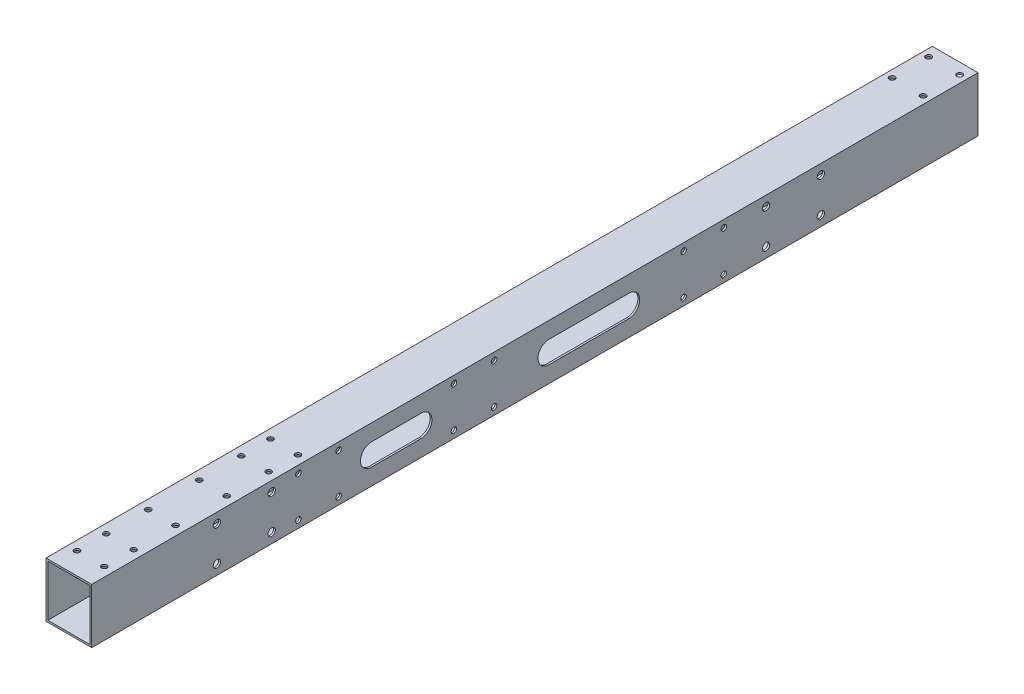
SolidWorks part; units mm, degrees
material "6063-T5"
ref_plane "前视基准面" through (0, 0, 0) normal (0, 0, 1) x (1, 0, 0)
ref_plane "上视基准面" through (0, 0, 0) normal (0, 1, 0) x (1, 0, 0)
ref_plane "右视基准面" through (0, 0, 0) normal (1, 0, 0) x (0, 0, -1)
sketch "草图1" plane through (0, 0, 0) normal (0, 0, 1) x (1, 0, 0)
  line L0 (-11.5, -14) -> (-11.5, 14)
  line L1 (-12.5, -15) -> (12.5, -15)
  line L2 (-12.5, -15) -> (-12.5, 15)
  line L3 (-12.5, 15) -> (12.5, 15)
  line L4 (12.5, -15) -> (12.5, 15)
  line L5 (0, 15) -> (0, -15) construction
  line L6 (-12.5, 0) -> (12.5, 0) construction
  line L7 (-11.5, 14) -> (11.5, 14)
  line L8 (11.5, -14) -> (11.5, 14)
  line L9 (-11.5, -14) -> (11.5, -14)
  point P0 (0, 0)
  dimension "D1" = 25
  dimension "D2" = 30
  dimension "D3" = 1
extrude "凸台-拉伸1" add sketch "草图1" along normal mid plane 485
sketch "草图4" plane through (0, 14, 0) normal (0, -1, 0) x (1, 0, 0)
  circle A0 centre (7.5, 214.55) radius 1.5 construction
  circle A1 centre (-7.5, 214.55) radius 1.5 construction
  circle A2 centre (7.5, 230.55) radius 1.5 construction
  circle A3 centre (-7.5, 230.55) radius 1.5 construction
  circle A4 centre (7.5, 214.55) radius 1.5
  circle A5 centre (-7.5, 214.55) radius 1.5
  circle A6 centre (7.5, 230.55) radius 1.5
  circle A7 centre (-7.5, 230.55) radius 1.5
  circle A8 centre (7.5, 124.65) radius 1.5 construction
  circle A9 centre (7.5, 140.65) radius 1.5 construction
  circle A10 centre (-7.5, 140.65) radius 1.5 construction
  circle A11 centre (-7.5, 124.65) radius 1.5 construction
  circle A12 centre (7.5, 124.65) radius 1.5
  circle A13 centre (7.5, 140.65) radius 1.5
  circle A14 centre (-7.5, 140.65) radius 1.5
  circle A15 centre (-7.5, 124.65) radius 1.5
extrude "切除-拉伸3" cut sketch "草图4" against normal mid plane 10
sketch "草图5" plane through (0, 15, 0) normal (0, 1, 0) x (1, 0, 0)
  line L0 (7.5, -140.65) -> (7.5, -214.55) construction
  line L1 (-7.5, -191.6) -> (7.5, -191.6) construction
  line L2 (-7.5, -191.6) -> (-7.5, -163.6) construction
  line L3 (-7.5, -163.6) -> (7.5, -163.6) construction
  line L4 (7.5, -191.6) -> (7.5, -163.6) construction
  line L5 (0, -163.6) -> (0, -191.6) construction
  line L6 (-7.5, -177.6) -> (7.5, -177.6) construction
  line L7 (12.5, -242.5) -> (12.5, 242.5) construction
  line L8 (-12.5, -242.5) -> (-12.5, 242.5) construction
  line L9 (7.5, -177.6) -> (-11.4517, -177.6) construction
  circle A0 centre (-7.5, -163.6) radius 1.525
  circle A1 centre (7.5, -163.6) radius 1.525
  circle A2 centre (-7.5, -191.6) radius 1.525
  circle A3 centre (7.5, -191.6) radius 1.525
  point P0 (0, -177.6)
  dimension "D4" = 3.05
  dimension "D1" = 5
  dimension "D2" = 5
  dimension "D3" = 28
extrude "切除-拉伸4" cut sketch "草图5" against normal mid plane 160
sketch "草图6" plane through (-12.5, 0, 0) normal (-1, 0, 0) x (0, 0, 1)
  line L0 (-79.9, 231.9) -> (-79.9, -138.1) construction
  line L1 (-104.9, 231.9) -> (-104.9, -138.1) construction
  line L2 (-79.9, 15) -> (-79.9, -15)
  line L3 (-104.9, 15) -> (-104.9, -15)
  line L4 (130.9, 231.9) -> (130.9, -138.1) construction
  line L5 (105.9, 231.9) -> (105.9, -138.1) construction
  line L6 (130.9, 15) -> (130.9, -15)
  line L7 (105.9, 15) -> (105.9, -15)
  line L8 (242.5, 15) -> (-242.5, 15) construction
  line L9 (242.5, -15) -> (-242.5, -15) construction
sketch "草图7" plane through (-12.5, 0, 0) normal (-1, 0, 0) x (0, 0, 1)
  line L0 (30.295, 205.9) -> (30.295, -116.65) construction
  line L1 (30.295, 15) -> (30.295, -15)
  line L2 (36.295, -116.65) -> (36.295, 205.9)
  line L3 (-10.295, 205.9) -> (-10.295, -116.65)
  line L4 (36.295, -15) -> (36.295, 15)
  line L44 (242.5, -15) -> (-242.5, -15) construction
  line L45 (242.5, 15) -> (-242.5, 15) construction
  line L46 (36.295, -15) -> (30.295, -15)
  line L47 (36.295, 15) -> (30.295, 15)
  line L48 (33.295, 15) -> (33.295, -15) construction
  arc A2 (-10.295, -116.65) -> (36.295, -116.65) centre (13, -116.65) ccw
  arc A3 (36.295, 205.9) -> (-10.295, 205.9) centre (13, 205.9) ccw
  dimension "D1" = 0
sketch "草图8" plane through (0, 15, 0) normal (0, 1, 0) x (1, 0, 0)
  circle A0 centre (8.5, 236.5) radius 1.55 construction
  circle A1 centre (-8.5, 236.5) radius 1.55 construction
  circle A2 centre (-8.5, 216.5) radius 1.55 construction
  circle A3 centre (8.5, 216.5) radius 1.55 construction
  circle A4 centre (8.5, 236.5) radius 1.55
  circle A5 centre (-8.5, 236.5) radius 1.55
  circle A6 centre (-8.5, 216.5) radius 1.55
  circle A7 centre (8.5, 216.5) radius 1.55
extrude "切除-拉伸5" cut sketch "草图8" against normal blind 59
sketch "草图9" plane through (12.5, 0, 0) normal (1, 0, 0) x (0, 0, -1)
  circle A0 centre (103.4, -11) radius 1.505 construction
  circle A1 centre (103.4, 11) radius 1.505 construction
  circle A2 centre (81.4, 11) radius 1.505 construction
  circle A3 centre (81.4, -11) radius 1.505 construction
  circle A4 centre (103.4, -11) radius 1.505
  circle A5 centre (103.4, 11) radius 1.505
  circle A6 centre (81.4, 11) radius 1.505
  circle A7 centre (81.4, -11) radius 1.505
  circle A8 centre (-44.295, -11) radius 1.505 construction
  circle A9 centre (-44.295, 11) radius 1.505 construction
  circle A10 centre (-22.295, 11) radius 1.505 construction
  circle A11 centre (-22.295, -11) radius 1.505 construction
  circle A12 centre (-44.295, -11) radius 1.505
  circle A13 centre (-44.295, 11) radius 1.505
  circle A14 centre (-22.295, 11) radius 1.505
  circle A15 centre (-22.295, -11) radius 1.505
  circle A16 centre (-107.4, -11) radius 1.505 construction
  circle A17 centre (-129.4, -11) radius 1.505 construction
  circle A18 centre (-107.4, 11) radius 1.505 construction
  circle A19 centre (-129.4, 11) radius 1.505 construction
  circle A20 centre (-107.4, -11) radius 1.505
  circle A21 centre (-129.4, -11) radius 1.505
  circle A22 centre (-107.4, 11) radius 1.505
  circle A23 centre (-129.4, 11) radius 1.505
extrude "切除-拉伸6" cut sketch "草图9" against normal blind 51
sketch "草图10" plane through (-12.5, 0, 0) normal (-1, 0, 0) x (0, 0, 1)
  line L0 (-51.4, 0) -> (-7.705, 0) construction
  line L1 (-51.4, 6) -> (-7.705, 6)
  line L2 (-51.4, -6) -> (-7.705, -6)
  line L3 (62.295, 0) -> (89.4, 0) construction
  line L4 (62.295, 6) -> (89.4, 6)
  line L5 (62.295, -6) -> (89.4, -6)
  arc A0 (-51.4, 6) -> (-51.4, -6) centre (-51.4, 0) ccw
  arc A1 (-7.705, -6) -> (-7.705, 6) centre (-7.705, 0) ccw
  circle A2 centre (-81.4, -11) radius 1.505 construction
  circle A3 centre (22.295, 11) radius 1.505 construction
  arc A4 (62.295, 6) -> (62.295, -6) centre (62.295, 0) ccw
  arc A5 (89.4, -6) -> (89.4, 6) centre (89.4, 0) ccw
  circle A6 centre (44.295, 11) radius 1.505 construction
  circle A7 centre (107.4, 11) radius 1.505 construction
  point P3 (-29.5525, 0)
  point P14 (75.8475, 0)
  dimension "D2" = 6
  dimension "D1" = 30
  dimension "D3" = 30
  dimension "D4" = 18
  dimension "D5" = 18
extrude "切除-拉伸7" cut sketch "草图10" against normal blind 146
sketch "草图11" plane through (12.5, 0, 0) normal (1, 0, 0) x (0, 0, -1)
  circle A0 centre (156.5, 9.5) radius 2 construction
  circle A1 centre (126.5, 9.5) radius 2 construction
  circle A2 centre (126.5, -9.5) radius 2 construction
  circle A3 centre (156.5, -9.5) radius 2 construction
  circle A4 centre (156.5, 9.5) radius 2
  circle A5 centre (126.5, 9.5) radius 2
  circle A6 centre (126.5, -9.5) radius 2
  circle A7 centre (156.5, -9.5) radius 2
extrude "切除-拉伸8" cut sketch "草图11" against normal mid plane 79
sketch "草图13" plane through (12.5, 0, 0) normal (1, 0, 0) x (0, 0, -1)
  circle A0 centre (-144, -9.5) radius 2 construction
  circle A1 centre (-144, 9.5) radius 2 construction
  circle A2 centre (-174, -9.5) radius 2 construction
  circle A3 centre (-174, 9.5) radius 2 construction
  circle A4 centre (-144, -9.5) radius 2
  circle A5 centre (-144, 9.5) radius 2
  circle A6 centre (-174, -9.5) radius 2
  circle A7 centre (-174, 9.5) radius 2
extrude "切除-拉伸11" cut sketch "草图13" against normal up to surface (25 mm away) up to face at (-12.5, -9.5, -158.5)
equation "\"D5@草图10\"=\"D4@草图10\""
equation "\"D1@草图10\"=\"D3@草图10\""
